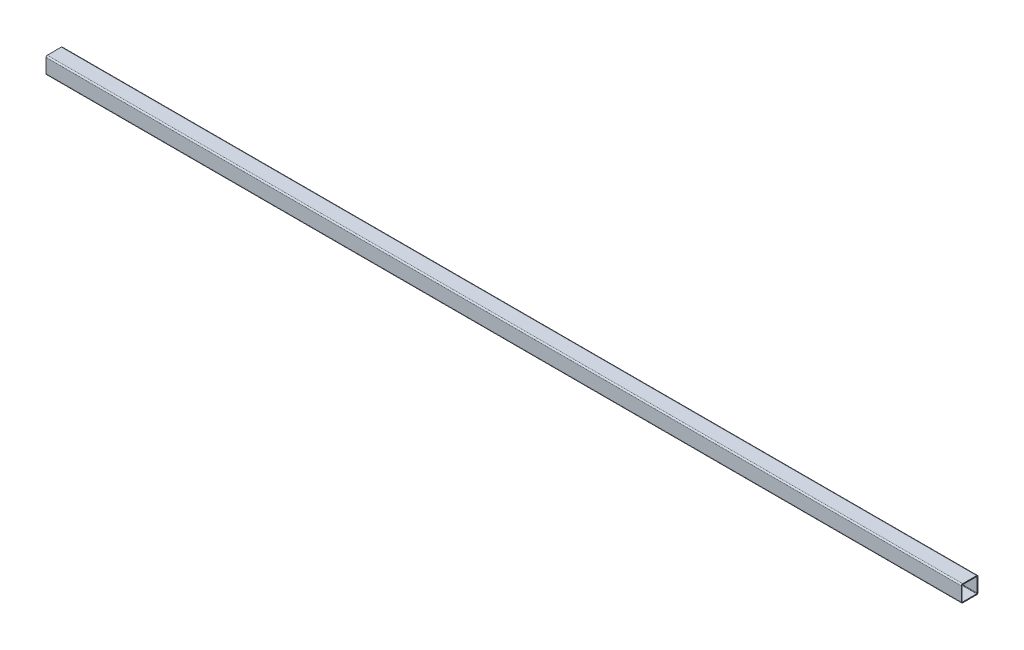
SolidWorks part; units mm, degrees
material "Plain Carbon Steel"
ref_plane "Front Plane" through (0, 0, 0) normal (0, 0, 1) x (1, 0, 0)
ref_plane "Top Plane" through (0, 0, 0) normal (0, 1, 0) x (1, 0, 0)
ref_plane "Right Plane" through (0, 0, 0) normal (1, 0, 0) x (0, 0, -1)
sketch "Sketch1" plane through (0, 0, 0) normal (1, 0, 0) x (0, 0, -1)
  line L0 (0, 2.54) -> (0, 29.21)
  line L1 (-2.54, 31.75) -> (-29.21, 31.75)
  line L2 (-31.75, 29.21) -> (-31.75, 2.54)
  line L3 (-29.21, 0) -> (-2.54, 0)
  line L4 (-1.651, 2.54) -> (-1.651, 29.21)
  line L5 (-2.54, 30.099) -> (-29.21, 30.099)
  line L6 (-30.099, 29.21) -> (-30.099, 2.54)
  line L7 (-29.21, 1.651) -> (-2.54, 1.651)
  arc A0 (-31.75, 2.54) -> (-29.21, 0) centre (-29.21, 2.54) ccw
  arc A1 (0, 2.54) -> (-2.54, 0) centre (-2.54, 2.54) cw
  arc A2 (0, 29.21) -> (-2.54, 31.75) centre (-2.54, 29.21) ccw
  arc A3 (-31.75, 29.21) -> (-29.21, 31.75) centre (-29.21, 29.21) cw
  arc A4 (-1.651, 29.21) -> (-2.54, 30.099) centre (-2.54, 29.21) ccw
  arc A5 (-30.099, 29.21) -> (-29.21, 30.099) centre (-29.21, 29.21) cw
  arc A6 (-30.099, 2.54) -> (-29.21, 1.651) centre (-29.21, 2.54) ccw
  arc A7 (-1.651, 2.54) -> (-2.54, 1.651) centre (-2.54, 2.54) cw
  point P12 (0, 0)
  point P15 (0, 31.75)
  point P18 (-31.75, 31.75)
  dimension "D3" = 2.54
  dimension "D1" = 31.75
  dimension "D2" = 31.75
  dimension "D4" = 1.651
extrude "Boss-Extrude1" add sketch "Sketch1" along normal blind 698.5
scale "Scale1" scale about centroid uniform scaling no x scale factor 1 y scale factor 0.4 z scale factor 0.4
sketch "Sketch2" plane through (0, 0, 9.525) normal (0, 0, -1) x (-1, 0, 0)
  line L0 (-698.5, 9.525) -> (0, 9.525) construction
  point P4 (-349.25, 9.525)
